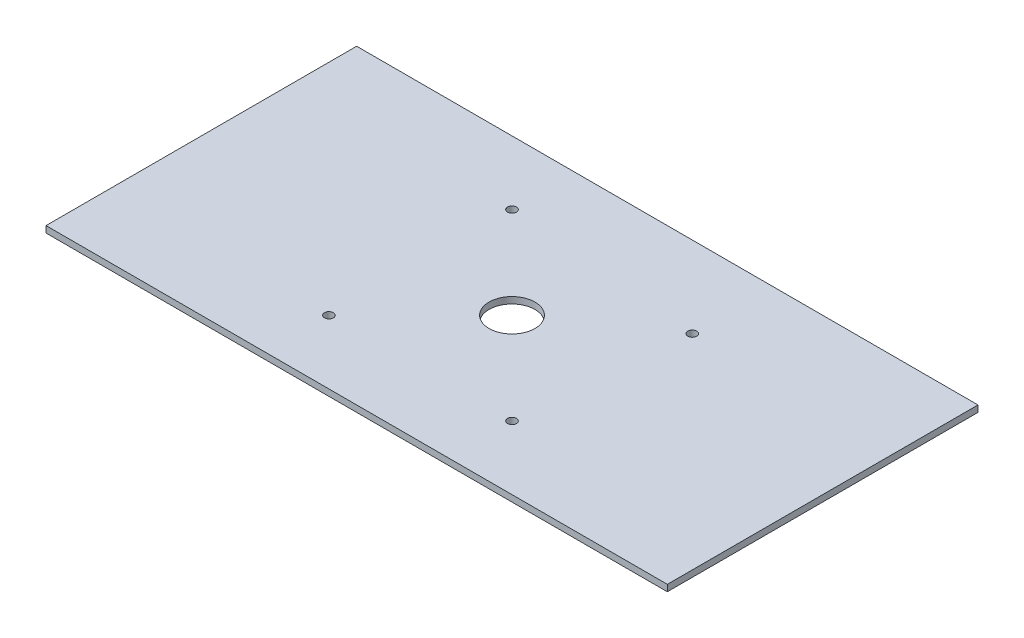
SolidWorks part; units mm, degrees
ref_plane "Front Plane" through (0, 0, 0) normal (0, 0, 1) x (1, 0, 0)
ref_plane "Top Plane" through (0, 0, 0) normal (0, 1, 0) x (1, 0, 0)
ref_plane "Right Plane" through (0, 0, 0) normal (1, 0, 0) x (0, 0, -1)
sketch "Sketch1" plane through (0, 0, 0) normal (0, 1, 0) x (1, 0, 0)
  line L0 (0, 0) -> (-72.8442, 104.0323) construction
  line L1 (0, 0) -> (72.8442, 104.0323) construction
  line L2 (0, 0) -> (89.8026, -89.8026) construction
  line L3 (0, 0) -> (-89.8026, -89.8026) construction
  line L4 (0, 0) -> (0, 127) construction
  line L5 (0, 0) -> (0, -127) construction
  line L6 (-127, 0) -> (127, 0) construction
  line L7 (0, 0) -> (104.0323, -72.8442) construction
  line L8 (0, 0) -> (104.0323, 72.8442) construction
  line L9 (0, 0) -> (-89.8026, 89.8026) construction
  line L11 (-304.8, 152.4) -> (304.8, 152.4)
  line L12 (-304.8, 152.4) -> (-304.8, -152.4)
  line L13 (-304.8, -152.4) -> (304.8, -152.4)
  line L14 (304.8, 152.4) -> (304.8, -152.4)
  line L15 (-304.8, 152.4) -> (304.8, -152.4) construction
  line L16 (-304.8, -152.4) -> (304.8, 152.4) construction
  circle A0 centre (0, 0) radius 127 construction
  circle A1 centre (-89.8026, -89.8026) radius 4.4
  circle A2 centre (-89.8026, 89.8026) radius 4.4
  circle A3 centre (104.0323, 72.8442) radius 4.4
  circle A4 centre (89.8026, -89.8026) radius 4.4
  circle A5 centre (0, 0) radius 22.5
  dimension "D1" = 45
  dimension "D8" = 254
  dimension "D9" = 8.8
  dimension "D10" = 45
  dimension "D2" = 35
  dimension "D3" = 35
  dimension "D4" = 35
  dimension "D5" = 45
  dimension "D6" = 45
  dimension "D7" = 35
  dimension "D11" = 609.6
  dimension "D12" = 304.8
extrude "Boss-Extrude1" add sketch "Sketch1" along normal blind 6.35
